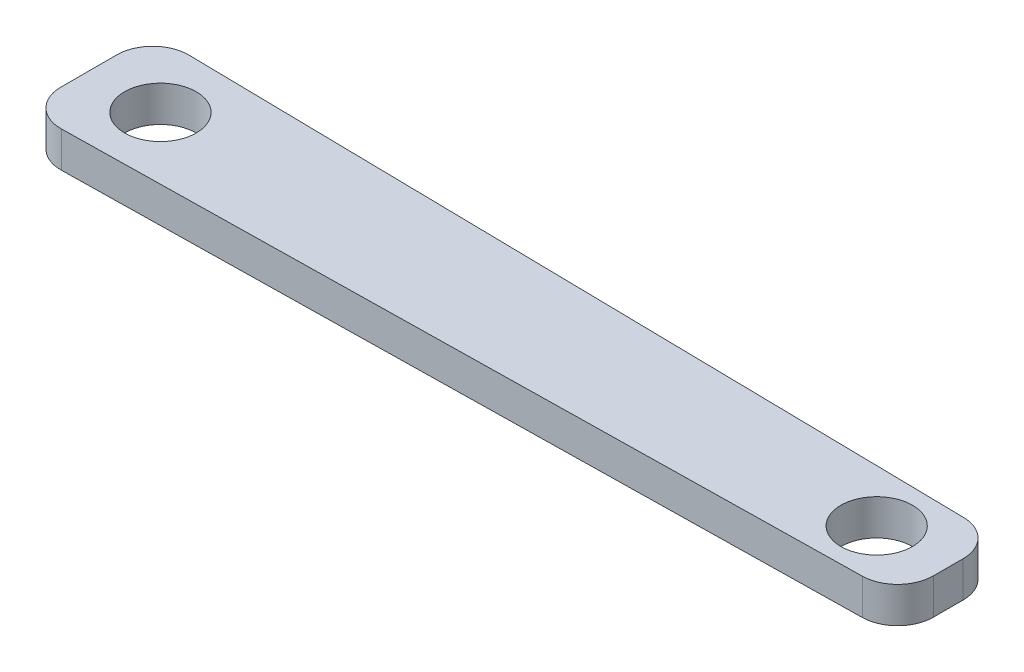
SolidWorks part; units mm, degrees
ref_plane "Alzado" through (0, 0, 0) normal (0, 0, 1) x (1, 0, 0)
ref_plane "Planta" through (0, 0, 0) normal (0, 1, 0) x (1, 0, 0)
ref_plane "Vista lateral" through (0, 0, 0) normal (1, 0, 0) x (0, 0, -1)
sketch "Croquis1" plane through (0, 0, 0) normal (0, 1, 0) x (1, 0, 0)
  line L0 (0, 0) -> (120, 2)
  line L1 (120, 2) -> (120, 16)
  line L2 (120, 16) -> (0, 18)
  line L3 (0, 18) -> (0, 0)
  line L4 (-0.0033, 9) -> (120, 9) construction
  circle A0 centre (10, 9) radius 5
  circle A1 centre (110, 9) radius 5
  dimension "D5" = 10
  dimension "D7" = 9
  dimension "D1" = 9
  dimension "D2" = 7
  dimension "D3" = 14
  dimension "D4" = 100
  dimension "D6" = 10
  dimension "D8" = 90
extrude "Saliente-Extruir1" add sketch "Croquis1" along normal blind 5
fillet "Redondeo1" radius 5 4 edges at (0, 2.5, -18) (120, 2.5, -16) (120, 2.5, -2) (0, 2.5, 0)
